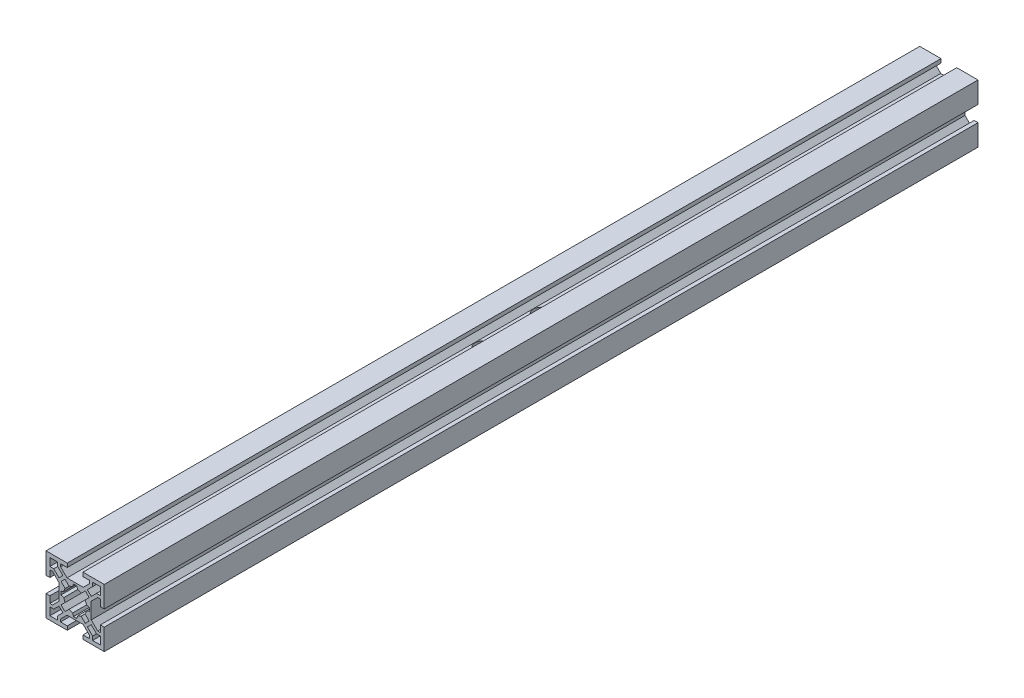
SolidWorks part; units mm, degrees
material "Liga 1060"
ref_plane "Plano frontal" through (0, 0, 0) normal (0, 0, 1) x (1, 0, 0)
ref_plane "Plano superior" through (0, 0, 0) normal (0, 1, 0) x (1, 0, 0)
ref_plane "Plano direito" through (0, 0, 0) normal (1, 0, 0) x (0, 0, -1)
ref_plane "Plano1" through (0, 0, 100) normal (0, 0, 1) x (1, 0, 0)
sketch "Esboço1" plane through (0, 0, 0) normal (0, 0, 1) x (1, 0, 0)
  line L0 (0, 0) -> (-15, -15) construction
  line L1 (-13, -4.05) -> (-15, -4.05)
  line L2 (-11.6273, -7.5) -> (-8.3, -4.1727)
  line L3 (-15, -15) -> (-4.05, -15)
  line L4 (-11.6273, -7.5) -> (-13, -7.5)
  line L5 (-7.5, -13) -> (-4.05, -13)
  line L6 (-7.2393, -5.2334) -> (-5.1254, -3.1194)
  line L7 (-8.3, -4.1727) -> (-8.3, 4.1727)
  line L8 (-11.006, -9) -> (-13, -9)
  line L9 (-13, -13) -> (-9, -13)
  line L10 (-13, -13) -> (-13, -9)
  line L11 (-13, -7.5) -> (-13, -4.05)
  line L12 (-15, -15) -> (-15, -4.05)
  line L13 (0, 0) -> (0, -8.3) construction
  line L14 (0, 0) -> (-8.3, 0) construction
  line L15 (7.2393, -5.2334) -> (5.2334, -7.2393)
  line L16 (4.05, -13) -> (4.05, -15)
  line L17 (-9, -11.006) -> (-9, -13)
  line L18 (0, 0) -> (0, 7.3) construction
  line L19 (7.5, -11.6273) -> (4.1727, -8.3)
  line L20 (7.5, -11.6273) -> (7.5, -13)
  line L21 (5.2334, -7.2393) -> (3.1194, -5.1254)
  line L22 (9, -11.006) -> (9, -13)
  line L23 (15, -15) -> (15, -4.05)
  line L24 (13, -7.5) -> (13, -4.05)
  line L25 (13, -13) -> (13, -9)
  line L26 (13, -13) -> (9, -13)
  line L27 (11.006, -9) -> (13, -9)
  line L28 (-4.1727, -8.3) -> (4.1727, -8.3)
  line L29 (8.3, -4.1727) -> (8.3, 4.1727)
  line L30 (7.2393, -5.2334) -> (5.1254, -3.1194)
  line L31 (7.5, -13) -> (4.05, -13)
  line L32 (11.6273, -7.5) -> (13, -7.5)
  line L33 (15, -15) -> (4.05, -15)
  line L34 (11.6273, -7.5) -> (8.3, -4.1727)
  line L35 (13, -4.05) -> (15, -4.05)
  line L36 (-7.2393, 5.2334) -> (-5.2334, 7.2393)
  line L37 (-4.05, 13) -> (-4.05, 15)
  line L38 (-7.5, 11.6273) -> (-4.1727, 8.3)
  line L39 (-7.5, 11.6273) -> (-7.5, 13)
  line L40 (-5.2334, 7.2393) -> (-3.1194, 5.1254)
  line L41 (13, 4.05) -> (15, 4.05)
  line L42 (11.6273, 7.5) -> (8.3, 4.1727)
  line L43 (15, 15) -> (4.05, 15)
  line L44 (11.6273, 7.5) -> (13, 7.5)
  line L45 (7.5, 13) -> (4.05, 13)
  line L46 (7.2393, 5.2334) -> (5.1254, 3.1194)
  line L47 (-5.2334, -7.2393) -> (-3.1194, -5.1254)
  line L48 (-4.1727, 8.3) -> (4.1727, 8.3)
  line L49 (11.006, 9) -> (13, 9)
  line L50 (13, 13) -> (9, 13)
  line L51 (13, 13) -> (13, 9)
  line L52 (13, 7.5) -> (13, 4.05)
  line L53 (15, 15) -> (15, 4.05)
  line L54 (9, 11.006) -> (9, 13)
  line L55 (5.2334, 7.2393) -> (3.1194, 5.1254)
  line L56 (-7.5, -11.6273) -> (-7.5, -13)
  line L57 (7.5, 11.6273) -> (7.5, 13)
  line L58 (7.5, 11.6273) -> (4.1727, 8.3)
  line L59 (-9, 11.006) -> (-9, 13)
  line L60 (-7.5, -11.6273) -> (-4.1727, -8.3)
  line L61 (4.05, 13) -> (4.05, 15)
  line L62 (7.2393, 5.2334) -> (5.2334, 7.2393)
  line L63 (-15, 15) -> (-15, 4.05)
  line L64 (-13, 7.5) -> (-13, 4.05)
  line L65 (-13, 13) -> (-13, 9)
  line L66 (-13, 13) -> (-9, 13)
  line L67 (-11.006, 9) -> (-13, 9)
  line L68 (-7.2393, 5.2334) -> (-5.1254, 3.1194)
  line L69 (-4.05, -13) -> (-4.05, -15)
  line L70 (-7.5, 13) -> (-4.05, 13)
  line L71 (-11.6273, 7.5) -> (-13, 7.5)
  line L72 (-15, 15) -> (-4.05, 15)
  line L73 (-11.6273, 7.5) -> (-8.3, 4.1727)
  line L74 (-13, 4.05) -> (-15, 4.05)
  line L75 (-6.294, -8.3) -> (-8.3, -6.294)
  line L76 (-6.294, -8.3) -> (-9, -11.006)
  line L77 (-8.3, -6.294) -> (-11.006, -9)
  line L78 (-8.3, 6.294) -> (-11.006, 9)
  line L79 (-6.294, 8.3) -> (-8.3, 6.294)
  line L80 (-6.294, 8.3) -> (-9, 11.006)
  line L81 (6.294, 8.3) -> (9, 11.006)
  line L82 (6.294, 8.3) -> (8.3, 6.294)
  line L83 (8.3, 6.294) -> (11.006, 9)
  line L84 (6.294, -8.3) -> (9, -11.006)
  line L85 (6.294, -8.3) -> (8.3, -6.294)
  line L86 (8.3, -6.294) -> (11.006, -9)
  line L87 (5.8582, -1.2966) -> (7.3, -0.8598)
  line L88 (7.3, -0.8598) -> (7.3, 0.8598)
  line L89 (5.8582, 1.2966) -> (7.3, 0.8598)
  line L90 (-1.2966, -5.8582) -> (-0.8598, -7.3)
  line L91 (-0.8598, -7.3) -> (0.8598, -7.3)
  line L92 (1.2966, -5.8582) -> (0.8598, -7.3)
  line L93 (1.2966, 5.8582) -> (0.8598, 7.3)
  line L94 (0.8598, 7.3) -> (-0.8598, 7.3)
  line L95 (-1.2966, 5.8582) -> (-0.8598, 7.3)
  line L96 (-5.8582, 1.2966) -> (-7.3, 0.8598)
  line L97 (-7.3, 0.8598) -> (-7.3, -0.8598)
  line L98 (-5.8582, -1.2966) -> (-7.3, -0.8598)
  line L99 (-7.2393, -5.2334) -> (-5.2334, -7.2393)
  arc A0 (-5.1254, -3.1194) -> (-5.8582, -1.2966) centre (0, 0) cw
  arc A1 (5.1254, -3.1194) -> (5.8582, -1.2966) centre (0, 0) ccw
  arc A2 (-3.1194, 5.1254) -> (-1.2966, 5.8582) centre (0, 0) cw
  arc A3 (-3.1194, -5.1254) -> (-1.2966, -5.8582) centre (0, 0) ccw
  arc A4 (1.2966, -5.8582) -> (3.1194, -5.1254) centre (0, 0) ccw
  arc A5 (5.8582, 1.2966) -> (5.1254, 3.1194) centre (0, 0) ccw
  arc A6 (1.2966, 5.8582) -> (3.1194, 5.1254) centre (0, 0) cw
  arc A7 (-5.8582, 1.2966) -> (-5.1254, 3.1194) centre (0, 0) cw
  point P4 (6.2364, 6.2364)
  point P6 (-6.2364, -6.2364)
  point P17 (6.2364, -6.2364)
  point P41 (-6.2364, 6.2364)
  point P60 (8.3, 0)
  point P86 (-7.297, -7.297)
  point P112 (0, 7.3)
  point P116 (7.3, 0)
  point P118 (0, 0)
  point P123 (0, -7.3)
  point P128 (-7.3, 0)
  point P129 (0, 0)
  dimension "D5" = 6
  dimension "D1" = 2
  dimension "D2" = 8.1
  dimension "D3" = 15
  dimension "D4" = 6.7
  dimension "D6" = 5.8368
  dimension "D7" = 1.5
  dimension "D8" = 1.5
  dimension "D9" = 30
  dimension "D10" = 1
  dimension "D11" = 1.7196
  dimension "D12" = 2.5933
  dimension "D13" = 1.5
  dimension "D14" = 4
extrude "Ressalto-extrusão1" add sketch "Esboço1" against normal mid plane 450
sketch "Esboço2" plane through (0, 0, 0) normal (0, 1, 0) x (1, 0, 0)
  line L0 (0, -15) -> (0, 0) construction
  line L1 (0, 0) -> (15, 0) construction
  circle A0 centre (0, -15) radius 4
  circle A1 centre (0, 15) radius 4
  dimension "D1" = 8
  dimension "D2" = 30
extrude "Corte-extrusão1" cut sketch "Esboço2" against normal through all and the other way through all
